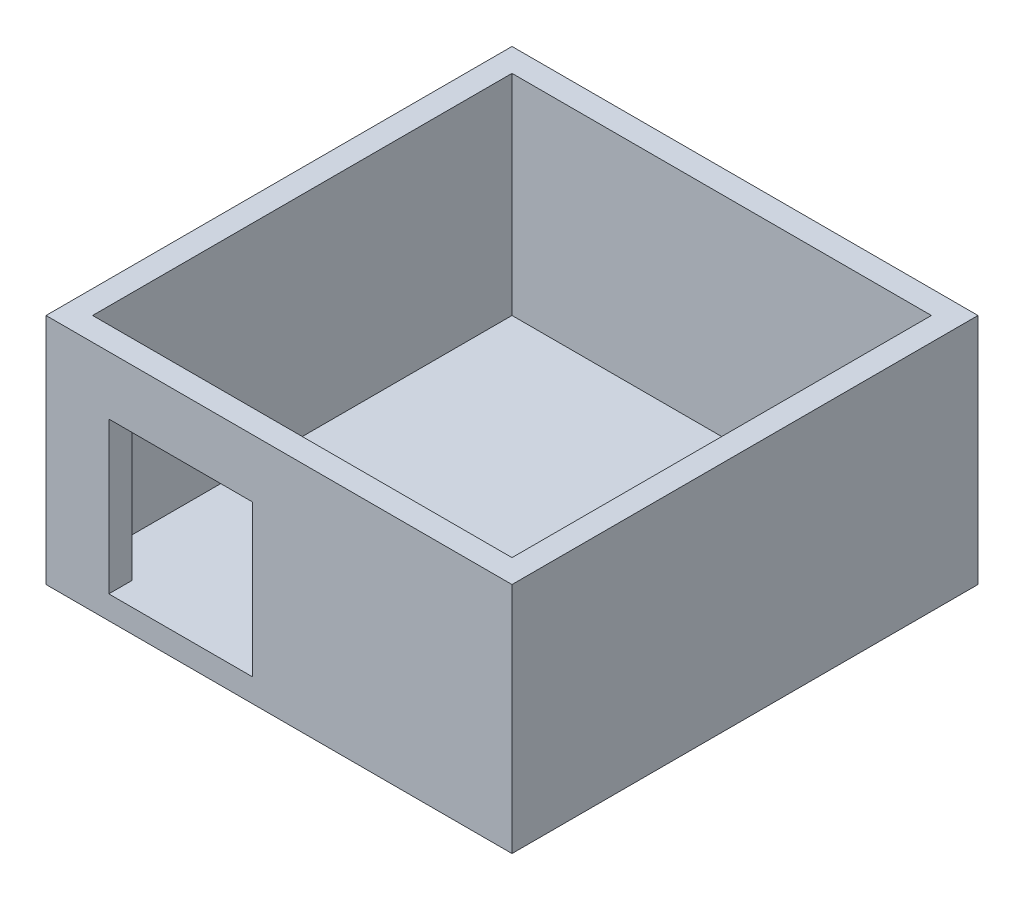
SolidWorks part; units mm, degrees
material "ABS"
ref_plane "Front Plane" through (0, 0, 0) normal (0, 0, 1) x (1, 0, 0)
ref_plane "Top Plane" through (0, 0, 0) normal (0, 1, 0) x (1, 0, 0)
ref_plane "Right Plane" through (0, 0, 0) normal (1, 0, 0) x (0, 0, -1)
sketch "Sketch4" plane through (0, 0, 0) normal (0, 1, 0) x (1, 0, 0)
  line L1 (-20, 20) -> (20, 20)
  line L2 (-20, 20) -> (-20, -20)
  line L3 (-20, -20) -> (20, -20)
  line L4 (20, 20) -> (20, -20)
  line L5 (-20, 20) -> (20, -20) construction
  line L6 (-20, -20) -> (20, 20) construction
  point P0 (0, 0)
  dimension "D2" = 40
  dimension "D3" = 40
extrude "Boss-Extrude3" add sketch "Sketch4" along normal blind 20
shell "Shell7" thickness 2
sketch "Sketch5" plane through (0, 0, 20) normal (0, 0, 1) x (1, 0, 0)
  line L0 (-20, 0) -> (20, 0) construction
  line L1 (-14.6097, 15) -> (-2.2897, 15)
  line L2 (-14.6097, 15) -> (-14.6097, 2)
  line L3 (-14.6097, 2) -> (-2.2897, 2)
  line L4 (-2.2897, 15) -> (-2.2897, 2)
  dimension "D1" = 12.32
  dimension "D2" = 13
  dimension "D3" = 2
extrude "Cut-Extrude1" cut sketch "Sketch5" against normal blind 2
